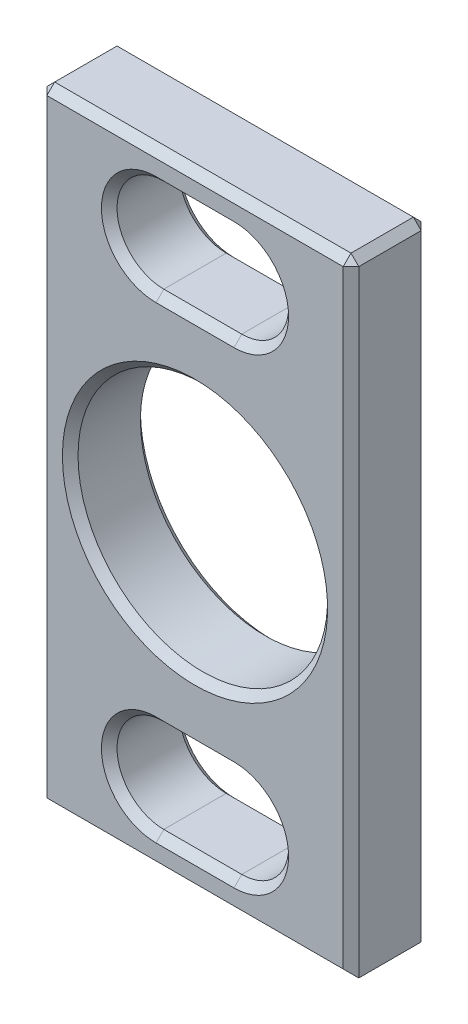
SolidWorks part; units mm, degrees
ref_plane "Plan de face" through (0, 0, 0) normal (0, 0, 1) x (1, 0, 0)
ref_plane "Plan de dessus" through (0, 0, 0) normal (0, 1, 0) x (1, 0, 0)
ref_plane "Plan de droite" through (0, 0, 0) normal (1, 0, 0) x (0, 0, -1)
sketch "Esquisse1" plane through (0, 0, 0) normal (0, 0, 1) x (1, 0, 0)
  line L1 (0, 0) -> (20, 0)
  line L2 (0, 0) -> (0, 40)
  line L3 (0, 40) -> (20, 40)
  line L4 (20, 0) -> (20, 40)
  dimension "D1" = 40
  dimension "D2" = 20
extrude "Boss.-Extru.1" add sketch "Esquisse1" along normal blind 5
sketch "Esquisse5" plane through (0, 0, 5) normal (0, 0, 1) x (1, 0, 0)
  line L0 (10, 40) -> (10, 0) construction
  line L1 (20, 40) -> (0, 40) construction
  line L2 (0, 0) -> (20, 0) construction
  circle A0 centre (10, 20) radius 8
  dimension "D1" = 16
extrude "Enlèv. mat.-Extru.2" cut sketch "Esquisse5" against normal blind 5
sketch "Esquisse6" plane through (0, 0, 5) normal (0, 0, 1) x (1, 0, 0)
  line L0 (7.5, 35) -> (12.5, 35) construction
  line L1 (7.5, 38) -> (12.5, 38)
  line L2 (7.5, 32) -> (12.5, 32)
  line L3 (20, 40) -> (0, 40) construction
  line L4 (10, 40) -> (10, 0) construction
  line L5 (0, 0) -> (20, 0) construction
  line L6 (10, 20) -> (0, 20) construction
  line L7 (0, 40) -> (0, 0) construction
  line L8 (7.5, 5) -> (12.5, 5) construction
  line L9 (7.5, 2) -> (12.5, 2)
  line L10 (7.5, 8) -> (12.5, 8)
  arc A0 (7.5, 38) -> (7.5, 32) centre (7.5, 35) ccw
  arc A1 (12.5, 32) -> (12.5, 38) centre (12.5, 35) ccw
  arc A2 (7.5, 2) -> (7.5, 8) centre (7.5, 5) cw
  arc A3 (12.5, 8) -> (12.5, 2) centre (12.5, 5) cw
  point P2 (10, 35)
  point P19 (10, 5)
  dimension "D1" = 6
  dimension "D2" = 2
  dimension "D3" = 5
extrude "Enlèv. mat.-Extru.3" cut sketch "Esquisse6" against normal through all
chamfer "Chanfrein1" distance 0.5 angle 45 28 edges at (4.5, 5, 5) (10, 2, 5) (15.5, 5, 5) (10, 8, 5) (10, 8, 0) (4.5, 5, 0) (10, 2, 0) (15.5, 5, 0) (4.5, 35, 5) (10, 32, 5) (15.5, 35, 5) (10, 38, 5) (10, 38, 0) (4.5, 35, 0) (10, 32, 0) (15.5, 35, 0) (18, 20, 5) (18, 20, 0) (0, 20, 0) (10, 40, 0) (0, 20, 5) (0, 40, 2.5) (10, 40, 5) (20, 40, 2.5) (20, 20, 5) (10, 0, 5) (0, 0, 2.5) (20, 20, 0)
